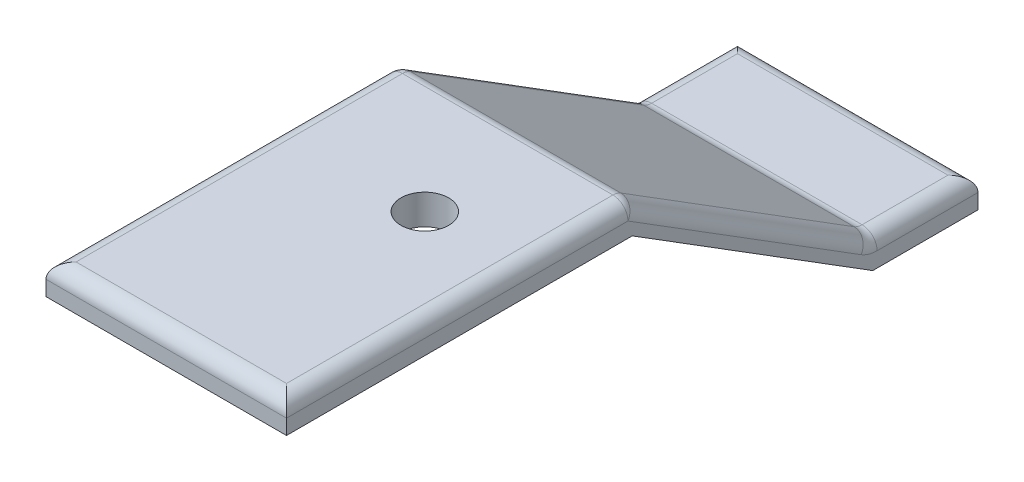
SolidWorks part; units mm, degrees
ref_plane "Front Plane" through (0, 0, 0) normal (0, 0, 1) x (1, 0, 0)
ref_plane "Top Plane" through (0, 0, 0) normal (0, 1, 0) x (1, 0, 0)
ref_plane "Right Plane" through (0, 0, 0) normal (1, 0, 0) x (0, 0, -1)
sketch "Sketch1" plane through (0, 0, 0) normal (0, 1, 0) x (1, 0, 0)
  line L1 (0, 0) -> (32, 0)
  line L2 (0, 0) -> (0, 92)
  line L3 (0, 92) -> (32, 92)
  line L4 (32, 0) -> (32, 92)
  dimension "D1" = 92
  dimension "D2" = 32
extrude "Boss-Extrude1" add sketch "Sketch1" along normal blind 4
sketch "Sketch2" plane through (0, 4, 0) normal (0, 1, 0) x (1, 0, 0)
  line L0 (0, 0) -> (32, 0) construction
  line L1 (0, 92) -> (0, 0) construction
  circle A0 centre (19.4, 31) radius 3.175
  dimension "D1" = 6.35
  dimension "D2" = 31
  dimension "D3" = 19.4
extrude "Cut-Extrude1" cut sketch "Sketch2" against normal blind 4
sketch "Sketch4" plane through (32, 0, 0) normal (1, 0, 0) x (0, 0, -1)
  line L0 (46, 0) -> (78, -20)
  line L1 (0, 0) -> (92, 0) construction
  line L2 (78, -20) -> (92, -20)
  line L3 (92, -20) -> (92, 4)
  line L4 (92, 4) -> (46, 4)
  line L5 (0, 4) -> (92, 4) construction
  line L6 (46, 4) -> (46, 0)
  line L7 (46, 4) -> (78, -16)
  line L8 (78, -16) -> (92, -16)
  line M8 (0, 0) -> (92, 0)
  dimension "D1" = 20
  dimension "D2" = 14
  dimension "D3" = 4
  dimension "D4" = 14
extrude "Boss-Extrude2" add sketch "Sketch4" against normal up to vertex (32 mm away) contours L8 L7 L0 L2 L3 M8 | L7 L6 M8
sketch "Sketch6" plane through (32, 0, 0) normal (1, 0, 0) x (0, 0, -1)
  line L0 (52.4, 0) -> (46, 4)
  line L1 (0, 4) -> (92, 4) construction
  line L2 (46, 4) -> (92, 4)
  line L3 (92, 4) -> (92, 0)
  line L4 (92, 0) -> (52.4, 0)
extrude "Cut-Extrude3" cut sketch "Sketch6" against normal through all
fillet "Fillet1" radius 2 10 edges at (16, -16, -78) (16, 4, -46) (32, -16, -85) (0, -16, -85) (0, -6, -62) (32, -6, -62) (0, 4, -23) (32, 4, -23) (16, 4, 0) (16, -16, -92)
